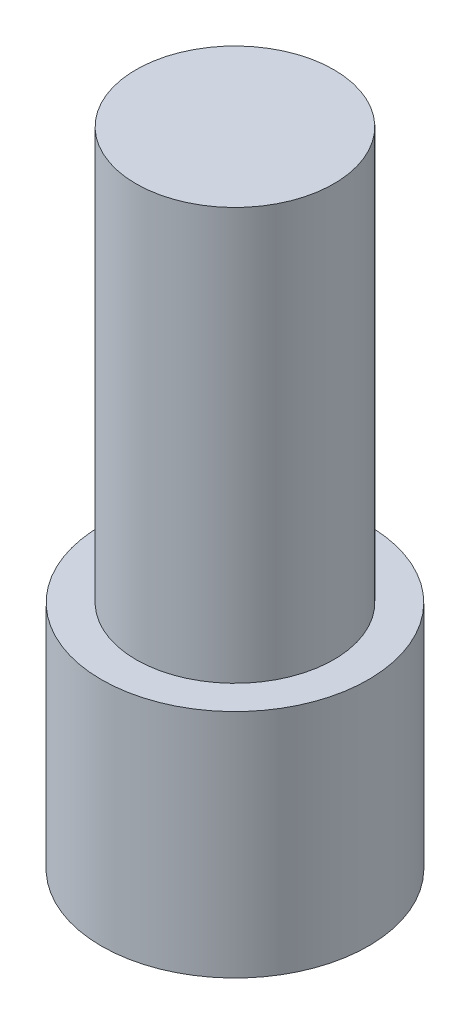
SolidWorks part; units mm, degrees
ref_plane "Front Plane" through (0, 0, 0) normal (0, 0, 1) x (1, 0, 0)
ref_plane "Top Plane" through (0, 0, 0) normal (0, 1, 0) x (1, 0, 0)
ref_plane "Right Plane" through (0, 0, 0) normal (1, 0, 0) x (0, 0, -1)
sketch "Sketch1" plane through (0, 0, 0) normal (0, 1, 0) x (1, 0, 0)
  circle A0 centre (0, 0) radius 4.05
  dimension "D1" = 8.1
extrude "Boss-Extrude1" add sketch "Sketch1" along normal blind 7
sketch "Sketch2" plane through (0, 7, 0) normal (0, 1, 0) x (1, 0, 0)
  circle A0 centre (0, 0) radius 3
  dimension "D1" = 6
extrude "Boss-Extrude2" add sketch "Sketch2" along normal blind 12.5 contours A0
